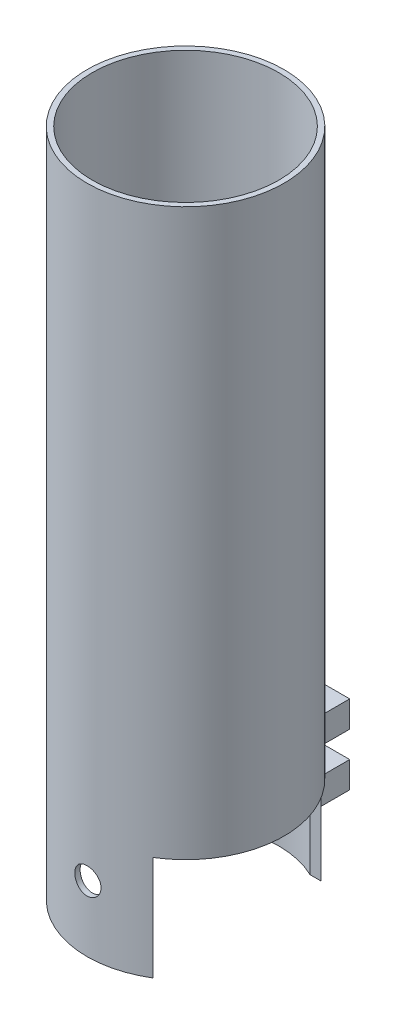
SolidWorks part; units mm, degrees
ref_plane "Front Plane" through (0, 0, 0) normal (0, 0, 1) x (1, 0, 0)
ref_plane "Top Plane" through (0, 0, 0) normal (0, 1, 0) x (1, 0, 0)
ref_plane "Right Plane" through (0, 0, 0) normal (1, 0, 0) x (0, 0, -1)
sketch "Sketch1" plane through (0, 0, 0) normal (0, 1, 0) x (1, 0, 0)
  circle A0 centre (0, 0) radius 37.5
  circle A1 centre (0, 0) radius 35.5
  dimension "D1" = 75
  dimension "D2" = 71
extrude "Boss-Extrude1" add sketch "Sketch1" along normal blind 255
sketch "Sketch2" plane through (0, 0, 0) normal (0, 0, 1) x (1, 0, 0)
  circle A0 centre (0, 25) radius 5
  dimension "D1" = 10
  dimension "D2" = 25
extrude "Cut-Extrude1" cut sketch "Sketch2" against normal through all both and the other way through all
ref_plane "Plane1" through (0, 0, -37.5) normal (0, 0, -1) x (-1, 0, 0)
sketch "Sketch3" plane through (0, 0, -37.5) normal (0, 0, -1) x (-1, 0, 0)
  line L0 (0, 43.0165) -> (0, 3.3239) construction
  line L1 (-5, 30) -> (5, 30)
  line L2 (-5, 30) -> (-5, 40)
  line L3 (-5, 40) -> (5, 40)
  line L4 (5, 30) -> (5, 40)
  line L5 (-5, 30) -> (5, 40) construction
  line L6 (-5, 40) -> (5, 30) construction
  line L7 (-5, 10) -> (5, 10)
  line L8 (-5, 10) -> (-5, 20)
  line L9 (-5, 20) -> (5, 20)
  line L10 (5, 10) -> (5, 20)
  line L11 (-5, 10) -> (5, 20) construction
  line L12 (-5, 20) -> (5, 10) construction
  circle A0 centre (0, 25) radius 5 construction
  point P0 (0, 35)
  point P5 (0, 15)
  dimension "D1" = 10
  dimension "D2" = 10
  dimension "D3" = 5
  dimension "D4" = 5
extrude "Boss-Extrude2" add sketch "Sketch3" along normal blind 20 separate body
sketch "Sketch4" plane through (0, 0, 0) normal (1, 0, 0) x (0, 0, -1)
  line L1 (-31.9778, -39.4027) -> (31.9778, -39.4027)
  line L2 (-31.9778, -39.4027) -> (-31.9778, 39.732)
  line L3 (-31.9778, 39.732) -> (31.9778, 39.732)
  line L4 (31.9778, -39.4027) -> (31.9778, 39.732)
  line L5 (-31.9778, -39.4027) -> (31.9778, 39.732) construction
  line L6 (-31.9778, 39.732) -> (31.9778, -39.4027) construction
extrude "Cut-Extrude2" cut sketch "Sketch4" along normal through all
